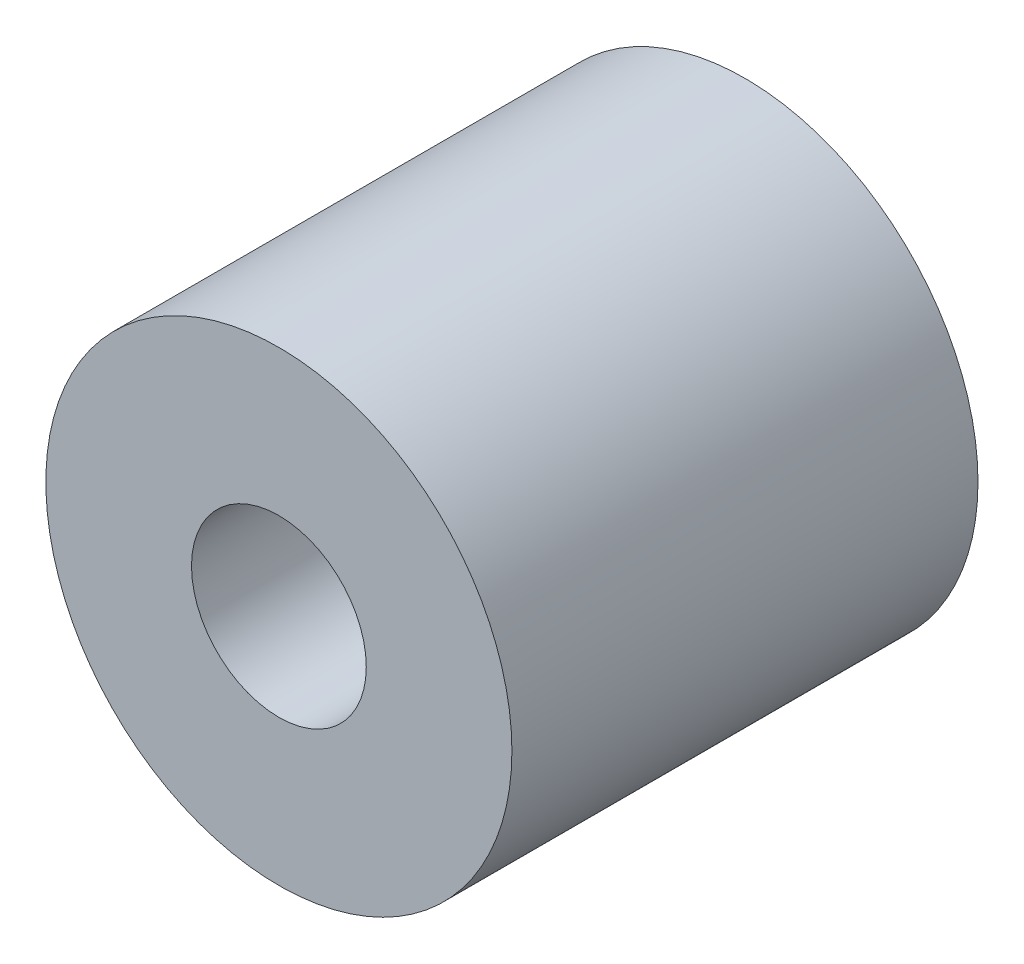
SolidWorks part; units mm, degrees
ref_plane "Front Plane" through (0, 0, 0) normal (0, 0, 1) x (1, 0, 0)
ref_plane "Top Plane" through (0, 0, 0) normal (0, 1, 0) x (1, 0, 0)
ref_plane "Right Plane" through (0, 0, 0) normal (1, 0, 0) x (0, 0, -1)
sketch "Sketch1" plane through (0, 0, 0) normal (0, 0, 1) x (1, 0, 0)
  circle A0 centre (0, 0) radius 12.7
  circle A1 centre (0, 0) radius 4.7625
  dimension "D1" = 25.4
  dimension "D2" = 9.525
extrude "Boss-Extrude1" add sketch "Sketch1" along normal blind 25.4
